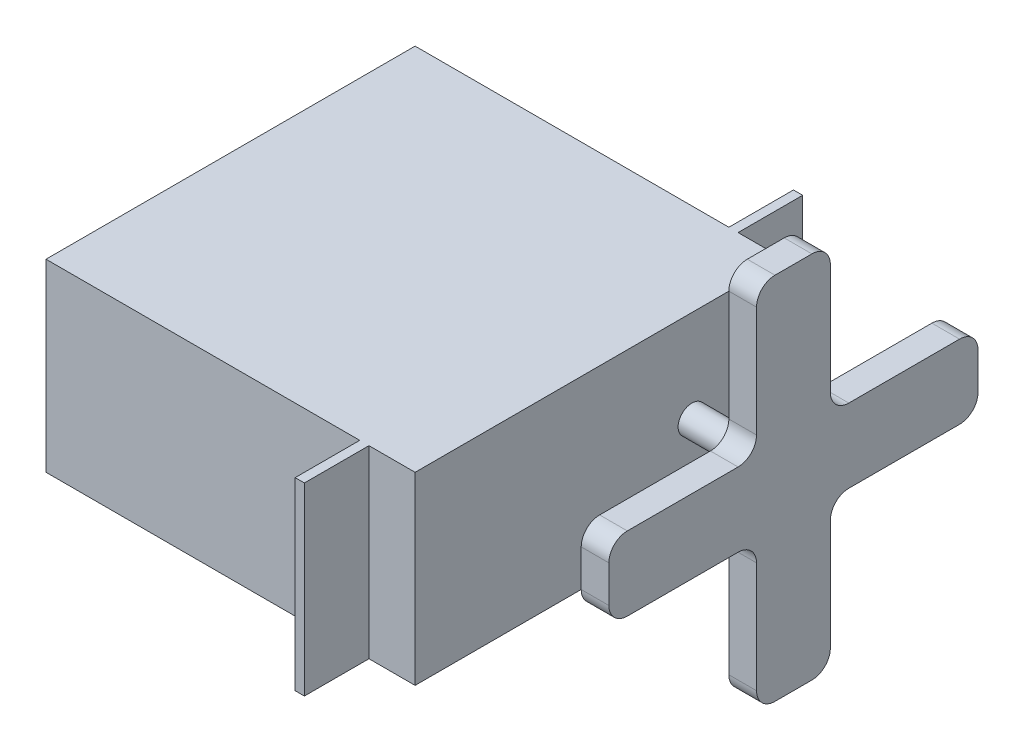
SolidWorks part; units mm, degrees
ref_plane "Front Plane" through (0, 0, 0) normal (0, 0, 1) x (1, 0, 0)
ref_plane "Top Plane" through (0, 0, 0) normal (0, 1, 0) x (1, 0, 0)
ref_plane "Right Plane" through (0, 0, 0) normal (1, 0, 0) x (0, 0, -1)
sketch "Sketch1" plane through (0, 0, 0) normal (0, 0, 1) x (1, 0, 0)
  line L1 (0, 0) -> (40, 0)
  line L2 (0, 0) -> (0, 20)
  line L3 (0, 20) -> (40, 20)
  line L4 (40, 0) -> (40, 20)
  dimension "D1" = 40
  dimension "D2" = 20
extrude "Boss-Extrude1" add sketch "Sketch1" along normal blind 40
sketch "Sketch2" plane through (40, 0, 0) normal (1, 0, 0) x (0, 0, -1)
  line L0 (-40, 10) -> (0, 10) construction
  line L1 (-40, 0) -> (-40, 20) construction
  line L2 (0, 0) -> (0, 20) construction
  circle A0 centre (-10, 10) radius 1.5
  dimension "D1" = 3
  dimension "D2" = 10
extrude "Boss-Extrude2" add sketch "Sketch2" along normal blind 8
sketch "Sketch4" plane through (48, 0, 0) normal (1, 0, 0) x (0, 0, -1)
  line L1 (-14, -10) -> (-6, -10)
  line L2 (-14, -10) -> (-14, 30)
  line L3 (-14, 30) -> (-6, 30)
  line L4 (-6, -10) -> (-6, 30)
  line L5 (-14, -10) -> (-6, 30) construction
  line L6 (-14, 30) -> (-6, -10) construction
  line L7 (-30, 6) -> (10, 6)
  line L8 (-30, 6) -> (-30, 14)
  line L9 (-30, 14) -> (10, 14)
  line L10 (10, 6) -> (10, 14)
  line L11 (-30, 6) -> (10, 14) construction
  line L12 (-30, 14) -> (10, 6) construction
  point P0 (-10, 10)
  point P6 (-10, 10)
  dimension "D1" = 8
  dimension "D2" = 40
  dimension "D3" = 8
  dimension "D4" = 40
extrude "Boss-Extrude4" add sketch "Sketch4" along normal blind 3 contours L7 L10 L9 L8 | L4 L3 L2 L1
fillet "Fillet1" radius 2 12 edges at (49.5, 30, 6) (49.5, 14, 6) (49.5, 6, -10) (49.5, 14, -10) (49.5, 6, 6) (49.5, -10, 6) (49.5, -10, 14) (49.5, 6, 14) (49.5, 30, 14) (49.5, 14, 14) (49.5, 14, 30) (49.5, 6, 30)
ref_plane "Plane1" through (34, 0, 0) normal (1, 0, 0) x (0, 0, -1)
sketch "Sketch6" plane through (34, 0, 0) normal (1, 0, 0) x (0, 0, -1)
  line L2 (-40, 20) -> (-47, 20)
  line L3 (-40, 20) -> (-40, 0)
  line L4 (-40, 0) -> (-47, 0)
  line L6 (-47, 20) -> (-47, 0)
  line L7 (0, 20) -> (7, 20)
  line L8 (0, 20) -> (0, 0)
  line L9 (0, 0) -> (7, 0)
  line L10 (7, 20) -> (7, 0)
  dimension "D1" = 7
  dimension "D2" = 7
extrude "Boss-Extrude5" add sketch "Sketch6" along normal blind 1
